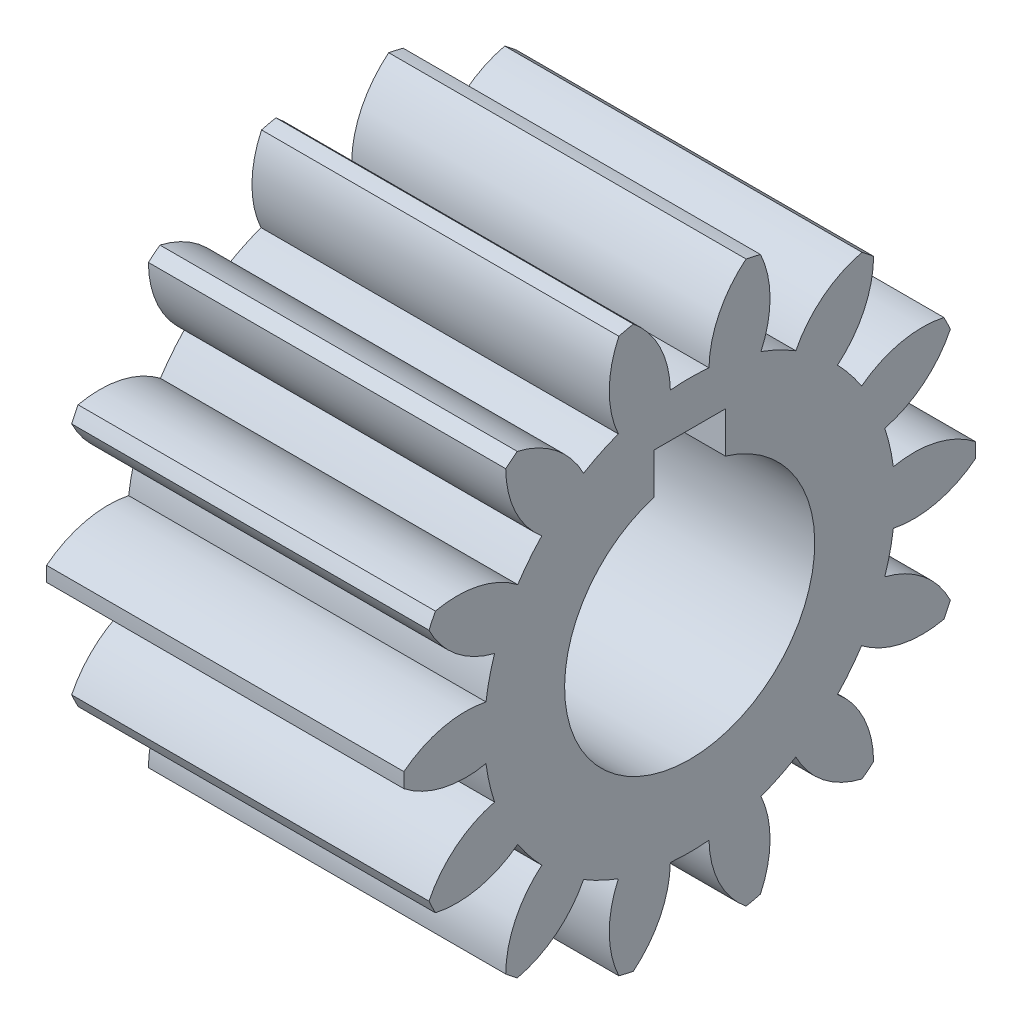
SolidWorks part; units mm, degrees
ref_plane "Plane1" through (0, 0, 0) normal (0, 0, 1) x (1, 0, 0)
ref_plane "Plane2" through (0, 0, 0) normal (0, 1, 0) x (1, 0, 0)
ref_plane "Plane3" through (0, 0, 0) normal (1, 0, 0) x (0, 0, -1)
sketch "HoldingSke" plane through (0, 0, 0) normal (0, 1, 0) x (1, 0, 0)
  line L0 (0, 0) -> (0.9703, -0.2419)
  line L1 (-15, 0) -> (100, 0) construction
  line L2 (0, 0) -> (-2.1039, 2.3779)
  line L3 (0, 0) -> (-11.863, 4.5341)
  line L4 (0, 0) -> (8.3795, 2.0892)
  line L5 (0, 0) -> (-46.8476, -17.4728)
  line L6 (0, 0) -> (-8.2896, -5.593)
  line L7 (-2.1039, 2.3779) -> (8.6586, 51.2059)
  line L8 (-76.2, 54.61) -> (-76.1, 54.61)
  line L9 (-71.009, 38.7566) -> (-53.1078, 45.2721)
  line L10 (-76.2, 71.12) -> (104.1128, 71.12)
  line L11 (0, 0) -> (-10, 0)
  line L12 (-76.2, 101.6) -> (-76.162, 101.6)
  line L13 (24.9733, 27.94) -> (52.9518, 28.4284)
  line L14 (24.9733, 27.94) -> (24.9743, 27.94)
  line L15 (24.9733, 27.94) -> (100.4006, 29.5858)
  line L16 (-63.627, -1) -> (-12.827, -1)
  circle A0 centre (0, 0) radius 0.4
  circle A1 centre (0, 0) radius 5.749
  circle A2 centre (0, 0) radius 37.5
  circle A3 centre (0, 0) radius 0.4
  dimension "MHD" = 11.498
  dimension "Hub_dia" = 75
  dimension "Bore" = 0.8
  dimension "MBD" = 0.8
  dimension "Num_teeth" = 14
  dimension "Pitch" = 1
  dimension "Overall_len" = 50
  dimension "Show_teeth" = 14
  dimension "Thickness" = 10
  dimension "OAL" = 50.0001
  dimension "T_dim" = 0.1
  dimension "Ap" = 20
  dimension "H" = 19.05
  dimension "Pitch_radius" = 180.3128
  dimension "Width" = 10
  dimension "Backlash" = 0.038
  dimension "Addendum_fac" = 1
  dimension "Dedendum_fac" = 1.25
  dimension "Clearance_fac" = 0.25
  dimension "Dedendum_add" = 0.001
  dimension "Module" = 1
sketch "BasProSke" plane through (0, 0, 0) normal (0, 1, 0) x (1, 0, 0)
  line L0 (-10, 0) -> (60, 0) construction
  line L1 (0, 0) -> (0, 8)
  line L2 (0, 0) -> (10, 0)
  line L3 (10, 0) -> (10, 8)
  line L4 (10, 8) -> (0, 8)
  dimension "Thickness" = 10
  dimension "Diameter" = 16
revolve "Base-Revolve" add sketch "BasProSke" angle 360 about L0
sketch "TooCutSke" plane through (0, 0, 0) normal (1, 0, 0) x (0, 0, -1)
  line L1 (0, 0) -> (0, 107) construction
  line L2 (0, 0) -> (-0.8502, 6.9482) construction
  line L3 (0, 0) -> (-3.0989, 13.5772) construction
  line L4 (-0.8502, 6.9482) -> (-1.5494, 6.7886) construction
  arc A0 (0.5404, 5.7235) -> (-0.5404, 5.7235) centre (0, 0) ccw
  arc A1 (1.6036, 7.8636) -> (-1.6036, 7.8636) centre (0, 0) ccw
  circle A2 centre (0, 0) radius 7 construction
  circle A3 centre (0, 0) radius 6.5778 construction
  arc A4 (-0.5404, 5.7235) -> (-1.6036, 7.8636) centre (-3.3398, 5.6669) ccw
  arc A5 (1.6036, 7.8636) -> (0.5404, 5.7235) centre (3.3398, 5.6669) ccw
  dimension "Root_dia" = 11.498
  dimension "Overcut_dia" = 16.0508
  dimension "Pitch_dia" = 14
  dimension "Base_dia" = 13.1557
  dimension "Flank_rad" = 2.8
  dimension "Half_ang" = 12.857
  dimension "Half_CT" = 0.7173
extrude "ToothCut" cut sketch "TooCutSke" along normal through all
fillet "Breaks" [suppressed] radius 0.02
fillet "RootFillets" [suppressed] radius 0.251
pattern_circular "TeethCuts" count 14 every 25.714 about axis through (-10, 0, 0) along (1, 0, 0) of "ToothCut", "RootFillets", "Breaks"
sketch "HubNeaOneSke" plane through (0, 0, 0) normal (-1, 0, 0) x (0, 0, 1)
  circle A0 centre (0, 0) radius 5.749
  dimension "Diameter" = 11.498
extrude "HubNearOne" [suppressed] add sketch "HubNeaOneSke" along normal blind 40.0001
sketch "HubNeaBotSke" plane through (0, 0, 0) normal (-1, 0, 0) x (0, 0, 1)
  circle A0 centre (0, 0) radius 5.749
  dimension "Diameter" = 11.498
extrude "HubNearBoth" [suppressed] add sketch "HubNeaBotSke" along normal blind 20
ref_plane "FarPln" through (10, 0, 0) normal (1, 0, 0) x (0, 0, -1)
sketch "HubFarSke" plane through (10, 0, 0) normal (1, 0, 0) x (0, 0, -1)
  circle A0 centre (0, 0) radius 5.749
  dimension "Diameter" = 11.498
extrude "HubFar" [suppressed] add sketch "HubFarSke" along normal blind 20
sketch "BorSke" plane through (0, 0, 0) normal (1, 0, 0) x (0, 0, -1)
  circle A0 centre (0, 0) radius 0.4
  dimension "Diameter" = 0.8
extrude "Bore" cut sketch "BorSke" along normal mid plane 100.0001
sketch "KeySke" plane through (0, 0, 0) normal (1, 0, 0) x (0, 0, -1)
  line L0 (-0.05, 0) -> (-0.05, 0.5)
  line L1 (-0.05, 0.5) -> (0.05, 0.5)
  line L2 (0.05, 0.5) -> (0.05, 0)
  line L3 (0, 0) -> (0, 34) construction
  line L4 (-0.05, 0) -> (0.05, 0)
  dimension "Offset" = 0.5
  dimension "Width" = 0.1
extrude "Keyway" [suppressed] cut sketch "KeySke" along normal mid plane 100.0001
pattern_circular "Keyway2" [suppressed] count 2 every 90 about axis through (-10, 0, 0) along (1, 0, 0)
sketch "Sketch1" plane through (10, 0, 0) normal (1, 0, 0) x (0, 0, -1)
  circle A0 centre (0, 0) radius 3.5
  dimension "D1" = 7
extrude "Cut-Extrude1" cut sketch "Sketch1" against normal blind 10
sketch "Sketch2" plane through (10, 0, 0) normal (1, 0, 0) x (0, 0, -1)
  line L0 (-1, 4.5) -> (-1, 2.5)
  line L1 (-1, 4.5) -> (1, 4.5)
  line L2 (-1, 2.5) -> (1, 2.5)
  line L3 (1, 4.5) -> (1, 2.5)
  line L4 (-1, 4.5) -> (1, 2.5) construction
  line L5 (-1, 2.5) -> (1, 4.5) construction
  line L6 (0, 3.5) -> (0, 0) construction
  circle A0 centre (0, 0) radius 3.5 construction
  point P1 (0, 3.5)
  dimension "D1" = 2
extrude "Cut-Extrude2" cut sketch "Sketch2" against normal blind 10
equation "' \"Module@HoldingSke\" = 6.35"
equation "' \"Num_teeth@HoldingSke\" = 12"
equation "' \"Ap@HoldingSke\" =  20"
equation "' \"Ap@HoldingSke\" = 20"
equation "' \"Width@HoldingSke\" = 0.5 * 25.4"
equation "' \"Hub_dia@HoldingSke\"= 1 * 25.4"
equation "' \"Hub_dia@HoldingSke\" = 1 * 25.4"
equation "' \"Overall_len@HoldingSke\" = 1.0 * 25.4"
equation "' \"Bore@HoldingSke\" = 0.75 * 25.4"
equation "' \"T_dim@HoldingSke\" = 0.1 * 25.4"
equation "' \"Width@KeySke\" = 0.25 * 25.4"
equation "' \"Show_teeth@HoldingSke\" = 13"
equation "' \"Backlash@HoldingSke\" = 0.009 * 25.4"
equation "' \"Addendum_fac@HoldingSke\" = 1.0"
equation "' \"Dedendum_fac@HoldingSke\" = 1.25"
equation "' \"Dedendum_add@HoldingSke\" = 0.00005 * 25.4"
equation "' \"Clearance_fac@HoldingSke\" = 0.25"
equation "\"Pitch@HoldingSke\" = 1 / \"Module@HoldingSke\""
equation "\"Overcut_dia@TooCutSke\" = (\"Num_teeth@HoldingSke\" + 2 * \"Addendum_fac@HoldingSke\") / \"Pitch@HoldingSke\" + 0.002 * 25.4"
equation "\"Pitch_dia@TooCutSke\" = \"Num_teeth@HoldingSke\" / \"Pitch@HoldingSke\""
equation "\"Base_dia@TooCutSke\" = \"Num_teeth@HoldingSke\" / \"Pitch@HoldingSke\" * cos((\"Ap@HoldingSke\"  * 3.14159265 / 180))"
equation "\"Root_dia@TooCutSke\" = (\"Num_teeth@HoldingSke\" + 2) / \"Pitch@HoldingSke\" - 2 * (\"Addendum_fac@HoldingSke\" + \"Dedendum_fac@HoldingSke\") / \"Pitch@HoldingSke\" - \"Dedendum_add@HoldingSke\" * 2"
equation "\"Half_ang@TooCutSke\" = 180 / \"Num_teeth@HoldingSke\""
equation "\"Half_CT@TooCutSke\" = \"Num_teeth@HoldingSke\" / \"Pitch@HoldingSke\" * sin((3.14159265 / 2 / \"Num_teeth@HoldingSke\")) / 2 - 7 * \"Backlash@HoldingSke\" / 4"
equation "\"Flank_rad@TooCutSke\" = \"Num_teeth@HoldingSke\" / \"Pitch@HoldingSke\" / 5"
equation "\"Radius@RootFillets\" = \"Clearance_fac@HoldingSke\" / \"Pitch@HoldingSke\" + \"Dedendum_add@HoldingSke\""
equation "\"Break_rad@Breaks\" = 0.02 / \"Pitch@HoldingSke\""
equation "\"Thickness@HoldingSke\" = \"Width@HoldingSke\""
equation "\"OAL@HoldingSke\" = \"Thickness@HoldingSke\""
equation "\"MHD@HoldingSke\" = (\"Num_teeth@HoldingSke\" + 2) / \"Pitch@HoldingSke\" - 2 * (\"Addendum_fac@HoldingSke\" + \"Dedendum_fac@HoldingSke\")  / \"Pitch@HoldingSke\" - \"Dedendum_add@HoldingSke\" * 2"
equation "\"MBD@HoldingSke\" = (\"Num_teeth@HoldingSke\" + 2) / \"Pitch@HoldingSke\" - 2 * (\"Addendum_fac@HoldingSke\" + \"Dedendum_fac@HoldingSke\")  / \"Pitch@HoldingSke\" - \"Dedendum_add@HoldingSke\" * 2 - 0.002 * 25.4"
equation "\"MHD@HoldingSke\" = ((sgn( \"MHD@HoldingSke\" - \"Hub_dia@HoldingSke\" )-1)*( \"MHD@HoldingSke\" - \"Hub_dia@HoldingSke\" ))/-2+ \"Hub_dia@HoldingSke\""
equation "\"MBD@HoldingSke\" = ((sgn( \"MBD@HoldingSke\" - \"Bore@HoldingSke\" )-1)*( \"MBD@HoldingSke\" - \"Bore@HoldingSke\" ))/-2+ \"Bore@HoldingSke\""
equation "\"OAL@HoldingSke\" = ((sgn( \"OAL@HoldingSke\" - \"Overall_len@HoldingSke\" )+1)*( \"OAL@HoldingSke\" - \"Overall_len@HoldingSke\" ))/2 + \"Overall_len@HoldingSke\" + 0.000002 * 25.4"
equation "\"Num_teeth@TeethCuts\" = int( \"Show_teeth@HoldingSke\" ) + 1"
equation "\"Num_teeth@TeethCuts\" = ((sgn( \"Num_teeth@TeethCuts\" - \"Num_teeth@HoldingSke\" )-1)*( \"Num_teeth@TeethCuts\" - \"Num_teeth@HoldingSke\" ))/-2+ \"Num_teeth@HoldingSke\""
equation "\"Num_teeth@TeethCuts\" = ((sgn( \"Num_teeth@TeethCuts\" - 2.0)+1)*( \"Num_teeth@TeethCuts\" - 2.0))/2 +2.0"
equation "\"Angle@TeethCuts\" = 360.0 / \"Num_teeth@HoldingSke\""
equation "\"Diameter@BasProSke\" = (\"Num_teeth@HoldingSke\" + 2 * \"Addendum_fac@HoldingSke\") / \"Pitch@HoldingSke\""
equation "\"Thickness@BasProSke\"  = \"Thickness@HoldingSke\""
equation "' \"Fillet_rad@BasProSke\" =  \"Thickness@HoldingSke\" * 0.05"
equation "' \"Fillet_rad@BasProSke\" = \"Thickness@HoldingSke\" * 0.05"
equation "\"MHD@HoldingSke\" = ((sgn( \"MHD@HoldingSke\" - \"Root_dia@TooCutSke\" )-1)*( \"MHD@HoldingSke\" - \"Root_dia@TooCutSke\" ))/-2+ \"Root_dia@TooCutSke\""
equation "\"Diameter@HubNeaOneSke\" = \"MHD@HoldingSke\""
equation "\"Length@HubNearOne\" = \"OAL@HoldingSke\" - \"Thickness@BasProSke\""
equation "\"Diameter@HubNeaBotSke\" = \"MHD@HoldingSke\""
equation "\"Length@HubNearBoth\" = ( \"OAL@HoldingSke\" - \"Thickness@BasProSke\" ) / 2.0"
equation "\"Thickness@FarPln\" = \"Thickness@BasProSke\""
equation "\"Diameter@HubFarSke\" = \"MHD@HoldingSke\""
equation "\"Length@HubFar\" = ( \"OAL@HoldingSke\" - \"Thickness@BasProSke\" ) / 2.0"
equation "\"Diameter@BorSke\" = \"MBD@HoldingSke\""
equation "\"D1@Bore\" = \"OAL@HoldingSke\" * 2.0"
equation "\"D1@Keyway\" = \"OAL@HoldingSke\" * 2.0"
equation "\"Offset@KeySke\" = \"T_dim@HoldingSke\" + \"MBD@HoldingSke\" / 2.0"
